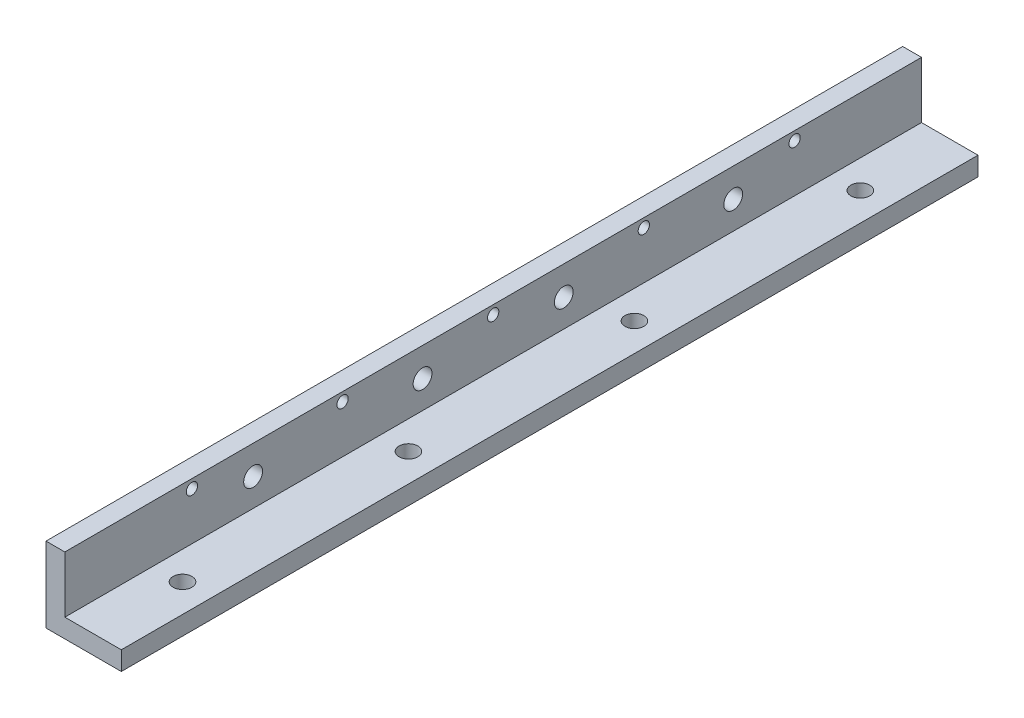
SolidWorks part; units mm, degrees
material "Aluminum"
ref_plane "Front Plane" through (0, 0, 0) normal (0, 0, 1) x (1, 0, 0)
ref_plane "Top Plane" through (0, 0, 0) normal (0, 1, 0) x (1, 0, 0)
ref_plane "Right Plane" through (0, 0, 0) normal (1, 0, 0) x (0, 0, -1)
sketch "Sketch1" plane through (0, 0, 0) normal (0, 0, 1) x (1, 0, 0)
  line L1 (0, 0) -> (5, 0)
  line L2 (0, 0) -> (0, 20)
  line L3 (0, 20) -> (5, 20)
  line L4 (5, 5) -> (5, 20)
  line L5 (0, 0) -> (20, 0)
  line L6 (0, 0) -> (0, 5)
  line L7 (5, 5) -> (20, 5)
  line L8 (20, 0) -> (20, 5)
  dimension "D1" = 20
  dimension "D2" = 20
  dimension "D3" = 5
  dimension "D4" = 5
extrude "Boss-Extrude1" add sketch "Sketch1" along normal blind 227.5 contours L5 L8 L7 L4 L3 L2 L1
hole_wizard "Tap Drill for M5x0.8 Tap1" positions "Sketch5" profile "Sketch4" hole size "M5x0.8" standard "ANSI Metric" end condition through all
sketch "Sketch5" plane through (0, 5, 0) normal (0, 1, 0) x (1, 0, 0)
  line L0 (20, -113.75) -> (58.4469, -113.75) construction
  line L1 (20, -227.5) -> (20, 0) construction
  point P0 (12.5, -203.75)
  point P2 (12.5, -143.75)
  point P4 (12.5, -83.75)
  point P6 (12.5, -23.75)
  dimension "D1" = 30
  dimension "D2" = 60
  dimension "D3" = 60
  dimension "D4" = 30
sketch "Sketch4" plane through (12.5, 5, 203.75) normal (1, 0, 0) x (0, 0, 1)
  line L0 (0, 0) -> (0, 5)
  line L1 (0, 5) -> (2.5, 5)
  line L2 (2.5, 5) -> (2.5, 0)
  line L5 (2.5, 0) -> (0, 0)
  line L11 (0, -6.35) -> (0, 107.95) construction
  dimension "Thru Hole Dia." = 5
  dimension "Thru Hole Depth" = 5
hole_wizard "Ø5.0 (5) Diameter Hole1" positions "Sketch8" profile "Sketch6" hole size "Ø5.0" standard "ANSI Metric" end condition through all
sketch "Sketch8" plane through (5, 0, 0) normal (1, 0, 0) x (0, 0, -1)
  line L0 (-227.5, 5) -> (-227.5, 20) construction
  line L1 (0, 5) -> (0, 20) construction
  point P0 (-177.5, 12.3462)
  point P2 (-132.5, 12.3462)
  point P6 (-95, 12.3462)
  point P8 (-50, 12.3462)
  dimension "D1" = 50
  dimension "D2" = 45
  dimension "D3" = 45
  dimension "D4" = 50
sketch "Sketch6" plane through (5, 12.3462, 177.5) normal (0, 1, 0) x (0, 0, -1)
  line L0 (0, 0) -> (0, 5)
  line L1 (0, 5) -> (2.5, 5)
  line L2 (2.5, 5) -> (2.5, 0)
  line L5 (2.5, 0) -> (0, 0)
  line L11 (0, -6.35) -> (0, 107.95) construction
  dimension "Thru Hole Dia." = 5
  dimension "Thru Hole Depth" = 5
sketch "Sketch9" plane through (0, 0, 0) normal (-1, 0, 0) x (0, 0, 1)
  circle A0 centre (33.7042, 17.6675) radius 1.5
  circle A1 centre (73.75, 17.6675) radius 1.5
  circle A2 centre (113.75, 17.6675) radius 1.5
  circle A3 centre (153.75, 17.6675) radius 1.5
  circle A4 centre (193.75, 17.6675) radius 1.5
extrude "Cut-Extrude1" cut sketch "Sketch9" against normal blind 29
